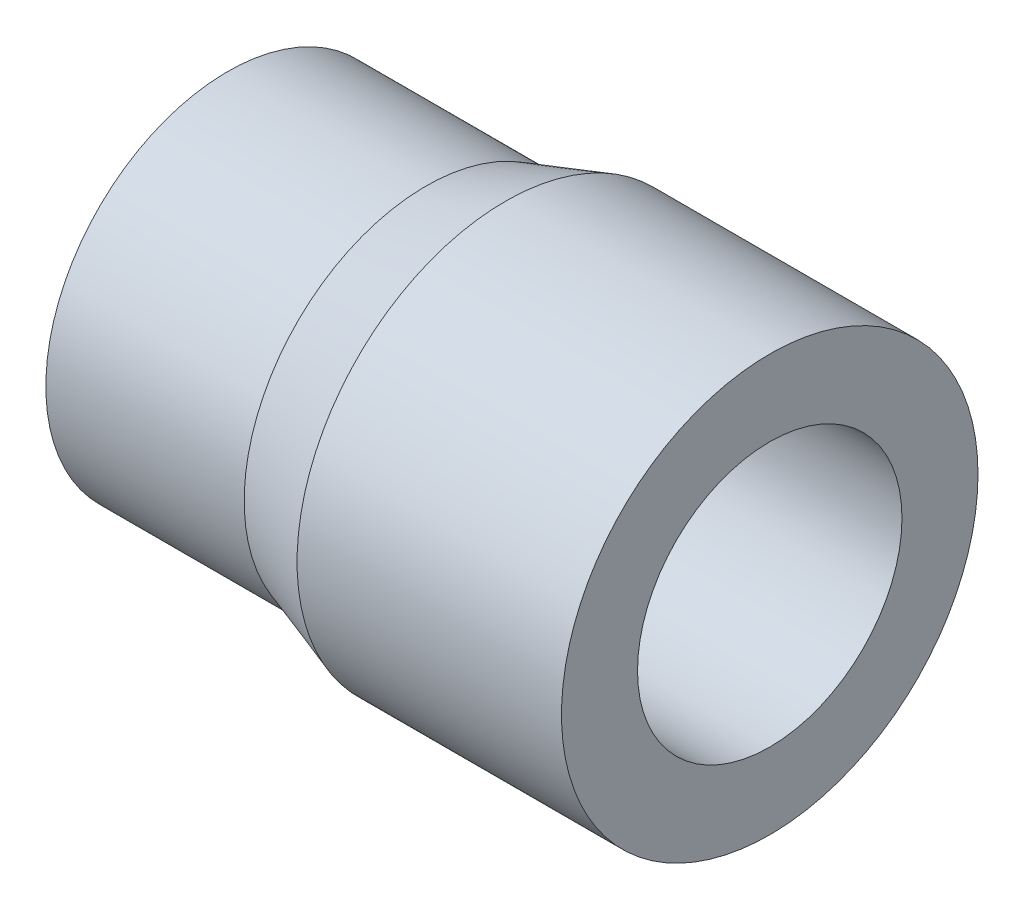
SolidWorks part; units mm, degrees
ref_plane "Alzado" through (0, 0, 0) normal (1, 0, 0) x (0, 1, 0)
ref_plane "Planta" through (0, 0, 0) normal (0, 0, 1) x (0, 1, 0)
ref_plane "Vista lateral" through (0, 0, 0) normal (0, 1, 0) x (-1, 0, 0)
sketch "Croquis1" plane through (0, 0, 0) normal (0, 1, 0) x (-1, 0, 0)
  line L0 (0, 3.15) -> (0, 2)
  line L1 (0, 2) -> (8.2, 2)
  line L2 (8.2, 2) -> (8.2, 2.75)
  line L3 (8.2, 2.75) -> (5.2, 2.75)
  line L4 (5.2, 2.75) -> (4, 3.15)
  line L5 (4, 3.15) -> (0, 3.15)
  line L6 (0, 0) -> (8.2, 0) construction
  dimension "D1" = 8.2
  dimension "D2" = 6.3
  dimension "D3" = 4
  dimension "D4" = 4
  dimension "D5" = 5.5
  dimension "D6" = 3
revolve "Revolución1" add sketch "Croquis1" angle 360 about L6
